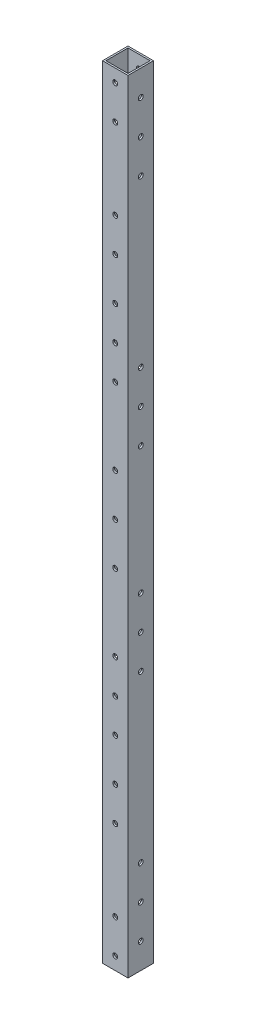
SolidWorks part; units mm, degrees
material "Thornel Mat VMA"
ref_plane "前视基准面" through (0, 0, 0) normal (0, 0, 1) x (1, 0, 0)
ref_plane "上视基准面" through (0, 0, 0) normal (0, 1, 0) x (1, 0, 0)
ref_plane "右视基准面" through (0, 0, 0) normal (1, 0, 0) x (0, 0, -1)
sketch "草图1" plane through (0, 0, 0) normal (0, 1, 0) x (1, 0, 0)
  line L1 (-7.5, -7.5) -> (7.5, -7.5)
  line L2 (-7.5, -7.5) -> (-7.5, 7.5)
  line L3 (-7.5, 7.5) -> (7.5, 7.5)
  line L4 (7.5, -7.5) -> (7.5, 7.5)
  line L5 (-7.5, -7.5) -> (7.5, 7.5) construction
  line L6 (-7.5, 7.5) -> (7.5, -7.5) construction
  point P0 (0, 0)
  dimension "D1" = 15
  dimension "D2" = 15
extrude "拉伸-薄壁1" add sketch "草图1" along normal blind 460 thin thin type one direction reverse wall 1
sketch "草图2" plane through (0, 0, 7.5) normal (0, 0, 1) x (1, 0, 0)
  line L0 (0, 0) -> (0, 460) construction
  line L1 (-7.5, 460) -> (7.5, 460) construction
  line L2 (-1000, 230) -> (49000, 230) construction
  line L3 (-7.5, 0) -> (7.5, 0) construction
  circle A0 centre (0, 7.5) radius 1.45
  circle A1 centre (0, 27.5) radius 1.45
  circle A2 centre (0, 432.5) radius 1.45
  circle A3 centre (0, 452.5) radius 1.45
  circle A4 centre (0, 140) radius 1.45
  circle A5 centre (0, 160) radius 1.45
  circle A6 centre (0, 120) radius 1.45
  circle A7 centre (0, 340) radius 1.45
  circle A8 centre (0, 300) radius 1.45
  circle A9 centre (0, 320) radius 1.45
  circle A10 centre (0, 230) radius 1.45
  circle A11 centre (0, 255) radius 1.45
  circle A12 centre (0, 205) radius 1.45
  circle A13 centre (0, 95) radius 1.45
  circle A14 centre (0, 365) radius 1.45
  circle A15 centre (0, 75) radius 1.45
  circle A16 centre (0, 385) radius 1.45
  point P8 (0, 230)
  dimension "D1" = 2.9
  dimension "D4" = 20
  dimension "D5" = 20
  dimension "D6" = 2.9
  dimension "D10" = 135
  dimension "D11" = 20
  dimension "D2" = 7.5
  dimension "D3" = 20
  dimension "D7" = 90
  dimension "D8" = 25
  dimension "D9" = 25
extrude "切除-拉伸1" cut sketch "草图2" against normal through all
sketch "草图3" plane through (7.5, 0, 0) normal (1, 0, 0) x (0, 0, -1)
  line L0 (0, 0) -> (0, 460) construction
  line L1 (-7.5, 460) -> (7.5, 460) construction
  line L2 (-1000, 230) -> (49000, 230) construction
  line L3 (-7.5, 0) -> (7.5, 0) construction
  circle A0 centre (0, 15) radius 1.45
  circle A1 centre (0, 35) radius 1.45
  circle A2 centre (0, 425) radius 1.45
  circle A3 centre (0, 445) radius 1.45
  circle A4 centre (0, 172.5) radius 1.45
  circle A5 centre (0, 192.5) radius 1.45
  circle A6 centre (0, 152.5) radius 1.45
  circle A7 centre (0, 307.5) radius 1.45
  circle A8 centre (0, 267.5) radius 1.45
  circle A9 centre (0, 287.5) radius 1.45
  circle A10 centre (0, 55) radius 1.45
  circle A11 centre (0, 405) radius 1.45
  point P12 (0, 230)
  dimension "D3" = 2.9
  dimension "D4" = 2.9
  dimension "D8" = 20
  dimension "D1" = 15
  dimension "D2" = 20
  dimension "D5" = 20
  dimension "D6" = 20
  dimension "D7" = 115
extrude "切除-拉伸2" cut sketch "草图3" against normal through all
